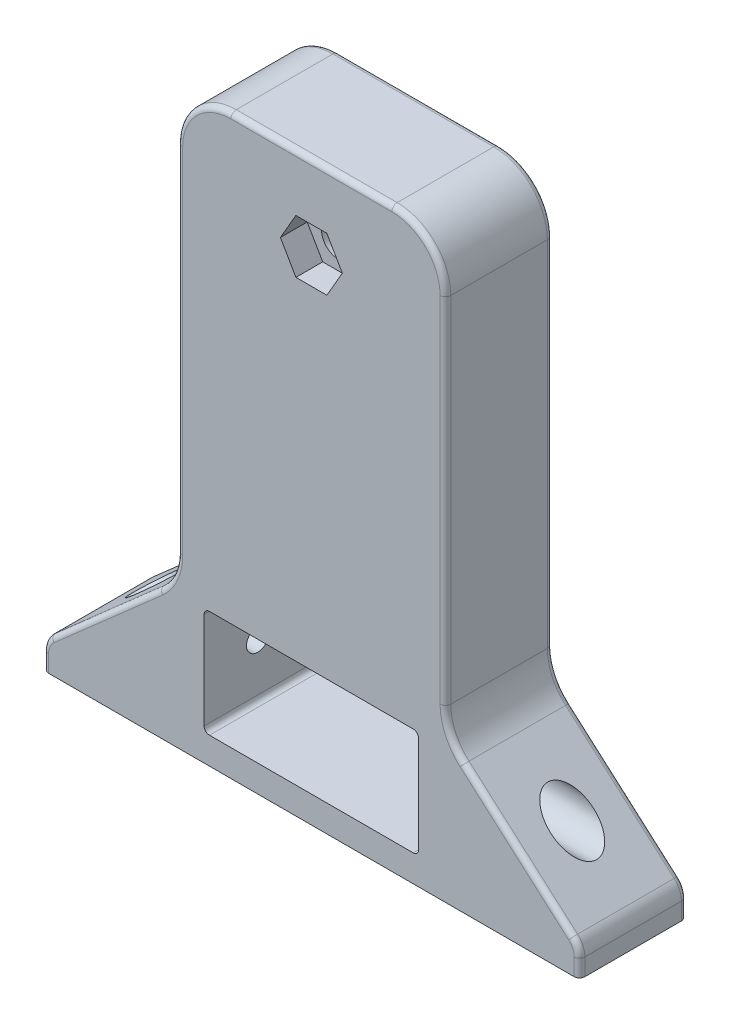
SolidWorks part; units mm, degrees
ref_plane "Front Plane" through (0, 0, 0) normal (0, 0, 1) x (1, 0, 0)
ref_plane "Top Plane" through (0, 0, 0) normal (0, 1, 0) x (1, 0, 0)
ref_plane "Right Plane" through (0, 0, 0) normal (1, 0, 0) x (0, 0, -1)
sketch "Sketch1" plane through (0, 0, 0) normal (0, 0, 1) x (1, 0, 0)
  line L0 (0, 10) -> (0, -10) construction
  line L1 (-19, 10) -> (19, 10)
  line L2 (-20, 9) -> (-20, -9)
  line L3 (-19, -10) -> (19, -10)
  line L4 (20, 9) -> (20, -9)
  line L5 (-20, 10) -> (20, -10) construction
  line L6 (-20, -10) -> (20, 10) construction
  line L7 (-50, -15) -> (50, -15)
  line L8 (-50, -15) -> (-50, -11.8083)
  line L9 (-48.6425, -8.8054) -> (-28.3937, 9.0135)
  line L10 (50, -15) -> (50, -11.8083)
  line L11 (48.6425, -8.8054) -> (28.3937, 9.0135)
  line L14 (-25, 16.5207) -> (-25, 82.5207)
  line L15 (-15, 92.5207) -> (15, 92.5207)
  line L16 (25, 16.5207) -> (25, 82.5207)
  arc A0 (19, 10) -> (20, 9) centre (19, 9) cw
  arc A1 (20, -9) -> (19, -10) centre (19, -9) cw
  arc A2 (-19, -10) -> (-20, -9) centre (-19, -9) cw
  arc A3 (-20, 9) -> (-19, 10) centre (-19, 9) cw
  arc A4 (28.3937, 9.0135) -> (25, 16.5207) centre (35, 16.5207) cw
  arc A5 (-28.3937, 9.0135) -> (-25, 16.5207) centre (-35, 16.5207) ccw
  arc A6 (25, 82.5207) -> (15, 92.5207) centre (15, 82.5207) ccw
  arc A7 (-15, 92.5207) -> (-25, 82.5207) centre (-15, 82.5207) ccw
  arc A8 (50, -11.8083) -> (48.6425, -8.8054) centre (46, -11.8083) ccw
  arc A9 (-50, -11.8083) -> (-48.6425, -8.8054) centre (-46, -11.8083) cw
  point P0 (0, 0)
  point P18 (0, 0)
  point P39 (-25, 92.5207)
  point P40 (50, -10)
  point P43 (-50, -10)
  dimension "D3" = 1
  dimension "D9" = 10
  dimension "D6" = 4
  dimension "D1" = 40
  dimension "D2" = 20
  dimension "D4" = 15
  dimension "D5" = 100
  dimension "D7" = 66
  dimension "D8" = 5
extrude "Boss-Extrude1" add sketch "Sketch1" along normal blind 20
sketch "Sketch8" plane through (0, 0, 0) normal (0, 0, -1) x (-1, 0, 0)
  line L0 (50, -15) -> (-50, -15) construction
  circle A0 centre (0, 77) radius 3.1
  point P3 (0, -15)
  dimension "D1" = 92
extrude "Cut-Extrude7" cut sketch "Sketch8" against normal up to next
fillet "Fillet1" radius 1 26 edges at (50, -13.4041, 20) (49.6449, -10.1605, 20) (38.5181, 0.1041, 20) (25.8878, 12.4014, 20) (-50, -13.4041, 20) (-49.6449, -10.1605, 20) (-38.5181, 0.1041, 20) (-25.8878, 12.4014, 20) (-25, 49.5207, 20) (-22.0711, 89.5917, 20) (0, 92.5207, 20) (22.0711, 89.5917, 20) (50, -13.4041, 0) (49.6449, -10.1605, 0) (38.5181, 0.1041, 0) (25.8878, 12.4014, 0) (-50, -13.4041, 0) (-49.6449, -10.1605, 0) (-38.5181, 0.1041, 0) (-25.8878, 12.4014, 0) (-25, 49.5207, 0) (-22.0711, 89.5917, 0) (0, 92.5207, 0) (22.0711, 89.5917, 0) (25, 49.5207, 20) (25, 49.5207, 0)
sketch "Sketch9" plane through (20, 0, 0) normal (-1, 0, 0) x (0, 0, 1)
  circle A0 centre (10, 0) radius 2.1
extrude "Cut-Extrude8" cut sketch "Sketch9" against normal up to next and the other way up to next
sketch "Sketch10" plane through (20, 0, 0) normal (-1, 0, 0) x (0, 0, 1)
  circle A0 centre (10, 0) radius 4
extrude "Cut-Extrude9" cut sketch "Sketch10" against normal up to next from offset 8 offset against normal yes
sketch "Sketch11" plane through (-20, 0, 0) normal (1, 0, 0) x (0, 0, -1)
  circle A0 centre (-10, 0) radius 4
extrude "Cut-Extrude10" cut sketch "Sketch11" against normal up to next from offset 8 offset against normal yes
sketch "Sketch12" plane through (0, 0, 0) normal (0, 0, -1) x (-1, 0, 0)
  line L1 (5.7735, 77) -> (2.8868, 82)
  line L2 (2.8868, 82) -> (-2.8868, 82)
  line L3 (-2.8868, 82) -> (-5.7735, 77)
  line L4 (-5.7735, 77) -> (-2.8868, 72)
  line L5 (-2.8868, 72) -> (2.8868, 72)
  line L6 (2.8868, 72) -> (5.7735, 77)
  circle A0 centre (0, 77) radius 5 construction
extrude "Cut-Extrude11" cut sketch "Sketch12" against normal blind 5
sketch "Sketch13" plane through (0, 0, 20) normal (0, 0, 1) x (1, 0, 0)
  line L1 (5.7735, 77) -> (2.8868, 82)
  line L2 (2.8868, 82) -> (-2.8868, 82)
  line L3 (-2.8868, 82) -> (-5.7735, 77)
  line L4 (-5.7735, 77) -> (-2.8868, 72)
  line L5 (-2.8868, 72) -> (2.8868, 72)
  line L6 (2.8868, 72) -> (5.7735, 77)
  circle A0 centre (0, 77) radius 5 construction
extrude "Cut-Extrude12" cut sketch "Sketch13" against normal blind 5
